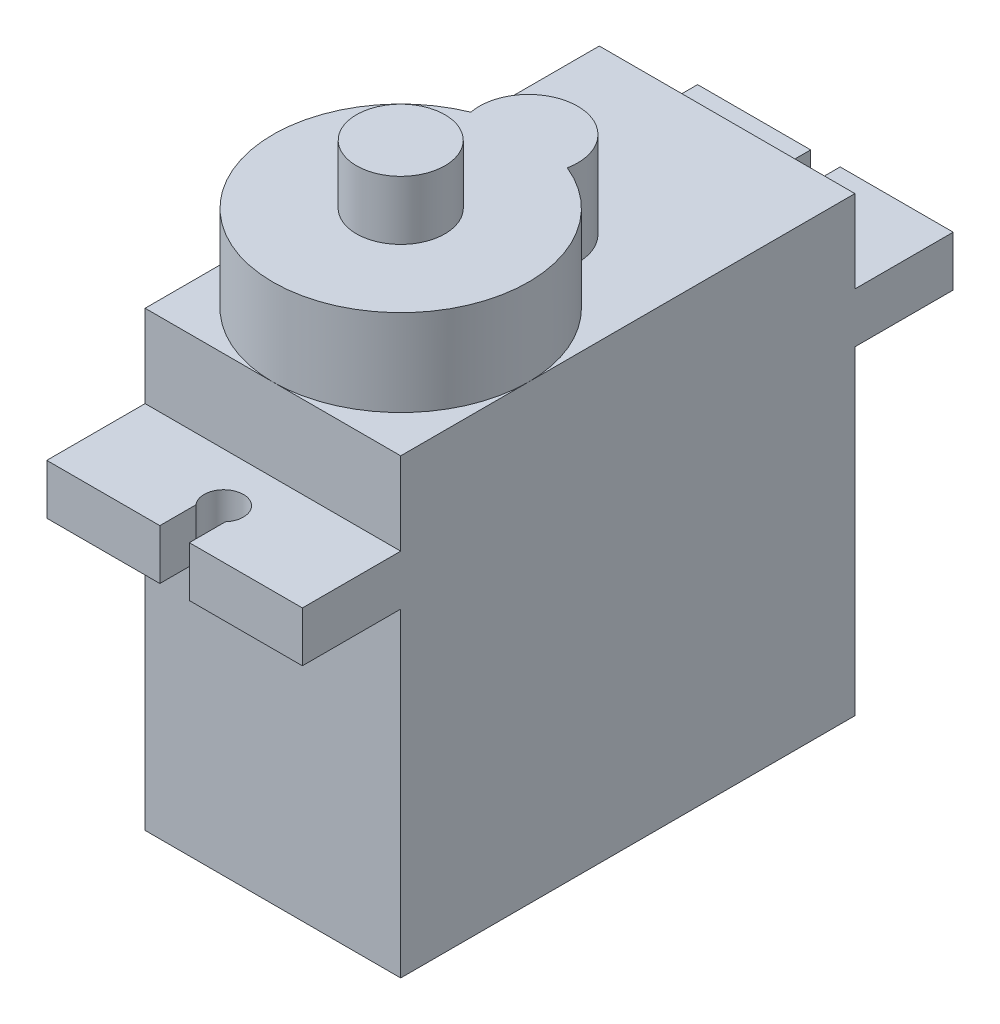
SolidWorks part; units mm, degrees
ref_plane "前视基准面" through (0, 0, 0) normal (0, 0, 1) x (1, 0, 0)
ref_plane "上视基准面" through (0, 0, 0) normal (0, 1, 0) x (1, 0, 0)
ref_plane "右视基准面" through (0, 0, 0) normal (1, 0, 0) x (0, 0, -1)
sketch "Sketch1" plane through (0, 0, 0) normal (1, 0, 0) x (0, 0, -1)
  line L0 (11.55, -4.2) -> (16.55, -4.2)
  line L1 (-11.55, 0) -> (11.55, 0)
  line L2 (-11.55, 0) -> (-11.55, -4.2)
  line L3 (-11.55, -23) -> (11.55, -23)
  line L4 (11.55, 0) -> (11.55, -4.2)
  line L5 (-16.55, -4.2) -> (-11.55, -4.2)
  line L6 (-16.55, -4.2) -> (-16.55, -6.75)
  line L7 (-16.55, -6.75) -> (-11.55, -6.75)
  line L8 (16.55, -4.2) -> (16.55, -6.75)
  line L9 (11.55, -6.75) -> (16.55, -6.75)
  line L10 (-11.55, -6.75) -> (-11.55, -23)
  line L11 (11.55, -6.75) -> (11.55, -23)
  dimension "D1" = 23.1
  dimension "D2" = 23
  dimension "D3" = 4.2
  dimension "D4" = 5
  dimension "D5" = 2.55
extrude "Boss-Extrude1" add sketch "Sketch1" along normal blind 13
sketch "Sketch2" plane through (0, 0, 0) normal (0, 1, 0) x (1, 0, 0)
  line L0 (13, -11.55) -> (0, -11.55) construction
  line L3 (13, 11.55) -> (13, -11.55) construction
  line L4 (0, 11.55) -> (0, -11.55) construction
  arc A0 (4.0467, 0.9692) -> (8.9533, 0.9692) centre (6.5, -5.05) ccw
  arc A1 (8.9533, 0.9692) -> (4.0467, 0.9692) centre (6.5, 1.45) ccw
  dimension "D1" = 5
extrude "Boss-Extrude2" add sketch "Sketch2" along normal blind 4.4
sketch "Sketch3" plane through (0, 4.4, 0) normal (0, 1, 0) x (1, 0, 0)
  circle A0 centre (6.5, -5.05) radius 2.25
  dimension "D1" = 4.5
extrude "Boss-Extrude3" add sketch "Sketch3" along normal blind 3
sketch "Sketch4" plane through (0, -4.2, 0) normal (0, 1, 0) x (1, 0, 0)
  line L0 (5.75, -16.55) -> (5.75, -14.7114)
  line L1 (13, -16.55) -> (0, -16.55) construction
  line L2 (7.25, -16.55) -> (7.25, -14.7114)
  line L3 (5.75, -16.55) -> (7.25, -16.55)
  line L4 (6.5, -14.05) -> (6.5, -16.55) construction
  arc A0 (7.25, -14.7114) -> (5.75, -14.7114) centre (6.5, -14.05) ccw
  dimension "D1" = 2
  dimension "D2" = 1.5
  dimension "D3" = 2.5
extrude "Cut-Extrude1" cut sketch "Sketch4" against normal up to next
mirror "Mirror1" about plane through (0, 0, 0) normal (0, 0, 1) of "Cut-Extrude1"
